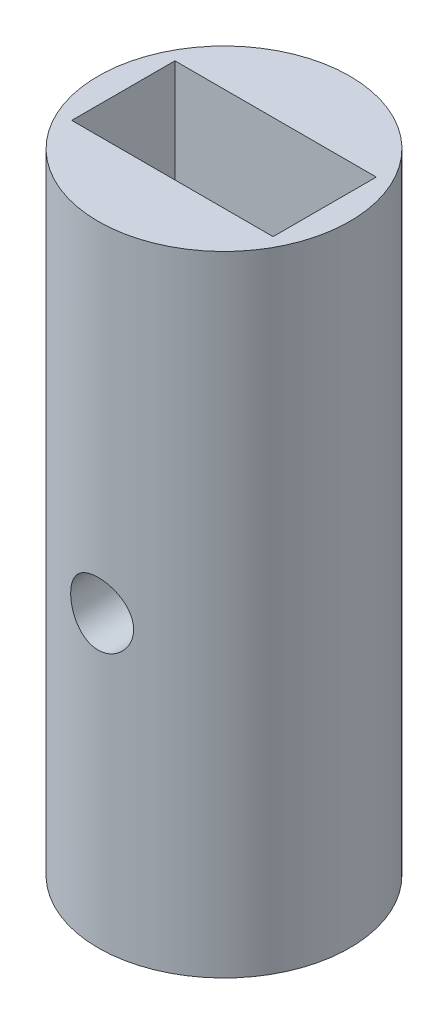
SolidWorks part; units mm, degrees
ref_plane "Front Plane" through (0, 0, 0) normal (0, 0, 1) x (1, 0, 0)
ref_plane "Top Plane" through (0, 0, 0) normal (0, 1, 0) x (1, 0, 0)
ref_plane "Right Plane" through (0, 0, 0) normal (1, 0, 0) x (0, 0, -1)
sketch "Sketch1" plane through (0, 0, 0) normal (0, 1, 0) x (1, 0, 0)
  circle A0 centre (0, 0) radius 5
  dimension "D1" = 10
extrude "Boss-Extrude1" add sketch "Sketch1" along normal blind 25
sketch "Sketch2" plane through (0, 0, 0) normal (0, 0, 1) x (1, 0, 0)
  line L0 (-4, 11.5) -> (-4, 25)
  line L1 (5, 25) -> (-5, 25) construction
  line L2 (4, 11.5) -> (4, 25)
  line L3 (-4, 25) -> (4, 25)
  arc A0 (-4, 11.5) -> (4, 11.5) centre (0, 11.5) ccw
  dimension "D1" = 8
  dimension "D2" = 13.5
extrude "Cut-Extrude1" cut sketch "Sketch2" against normal mid plane 4.1
ref_plane "Plane1" through (0, 0, 2.05) normal (0, 0, 1) x (1, 0, 0)
sketch "Sketch3" plane through (0, 0, 2.05) normal (0, 0, 1) x (1, 0, 0)
  circle A0 centre (0, 11.5) radius 1.25 construction
  circle A1 centre (0, 11.5) radius 1.25
extrude "Cut-Extrude2" cut sketch "Sketch3" against normal through all both and the other way through all
